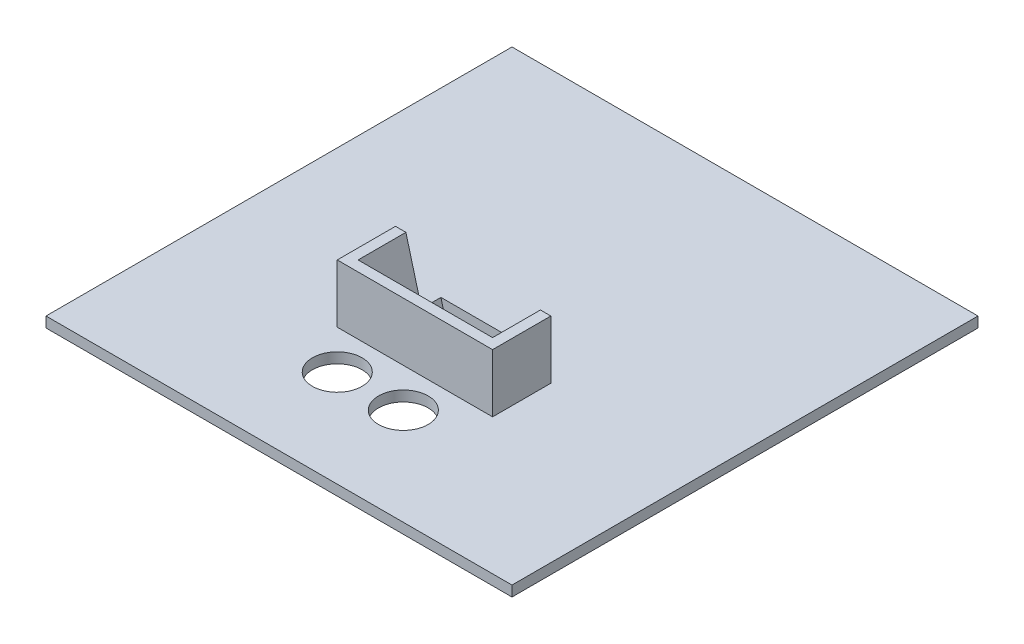
SolidWorks part; units mm, degrees
ref_plane "Front Plane" through (0, 0, 0) normal (0, 0, 1) x (1, 0, 0)
ref_plane "Top Plane" through (0, 0, 0) normal (0, 1, 0) x (1, 0, 0)
ref_plane "Right Plane" through (0, 0, 0) normal (1, 0, 0) x (0, 0, -1)
sketch "Sketch1" plane through (0, 0, 0) normal (0, 1, 0) x (1, 0, 0)
  line L1 (0, 0) -> (152.4, 0)
  line L2 (0, 0) -> (0, 152.4)
  line L3 (0, 152.4) -> (152.4, 152.4)
  line L4 (152.4, 0) -> (152.4, 152.4)
  dimension "D1" = 152.4
  dimension "D2" = 152.4
extrude "Boss-Extrude1" add sketch "Sketch1" along normal blind 3.4036
sketch "Sketch2" plane through (0, 3.4036, 0) normal (0, 1, 0) x (1, 0, 0)
  line L0 (0, 0) -> (152.4, 0) construction
  line L1 (0, 152.4) -> (0, 0) construction
  circle A0 centre (63.5, 31.75) radius 8.109
  circle A1 centre (85.1154, 31.75) radius 8.109
  dimension "D1" = 16.2179
  dimension "D2" = 16.2179
  dimension "D3" = 21.6154
  dimension "D4" = 0
  dimension "D5" = 31.75
  dimension "D6" = 63.5
extrude "Cut-Extrude1" cut sketch "Sketch2" against normal through all
sketch "Sketch3" plane through (0, 3.4036, 0) normal (0, 1, 0) x (1, 0, 0)
  line L0 (0, 152.4) -> (0, 0) construction
  line L1 (50.8, 44.45) -> (101.6, 44.45)
  line L2 (50.8, 44.45) -> (50.8, 63.5)
  line L3 (50.8, 63.5) -> (101.6, 63.5)
  line L4 (101.6, 44.45) -> (101.6, 63.5)
  line L6 (152.4, 0) -> (152.4, 152.4) construction
  circle A0 centre (63.5, 31.75) radius 8.109 construction
  dimension "D1" = 12.7
  dimension "D2" = 19.05
  dimension "D3" = 50.8
  dimension "D4" = 50.8
extrude "Boss-Extrude2" add sketch "Sketch3" along normal blind 19.05
sketch "Sketch4" plane through (0, 22.4536, 0) normal (0, 1, 0) x (1, 0, 0)
  line L0 (101.6, 63.5) -> (50.8, 63.5) construction
  line L1 (54.2036, 47.8536) -> (98.1964, 47.8536)
  line L2 (54.2036, 47.8536) -> (54.2036, 69.85)
  line L3 (54.2036, 69.85) -> (98.1964, 69.85)
  line L4 (98.1964, 47.8536) -> (98.1964, 69.85)
  line L5 (50.8, 63.5) -> (50.8, 44.45) construction
  line L6 (101.6, 44.45) -> (101.6, 63.5) construction
  line L7 (50.8, 44.45) -> (101.6, 44.45) construction
  dimension "D1" = 6.35
  dimension "D2" = 3.4036
  dimension "D3" = 3.4036
  dimension "D4" = 3.4036
extrude "Cut-Extrude2" cut sketch "Sketch4" against normal through all
draft "Draft1" type of draft neutral plane draft angle 15 faces to draft 3 face at (54.2036, 8.6191, -60.4012) face at (98.1964, 8.6191, -60.4012) face at (76.2, 11.2268, -47.8536) neutral plane through (0, 22.4536, 0) neutral plane normal (0, 1, 0) parameters "D1"=15
